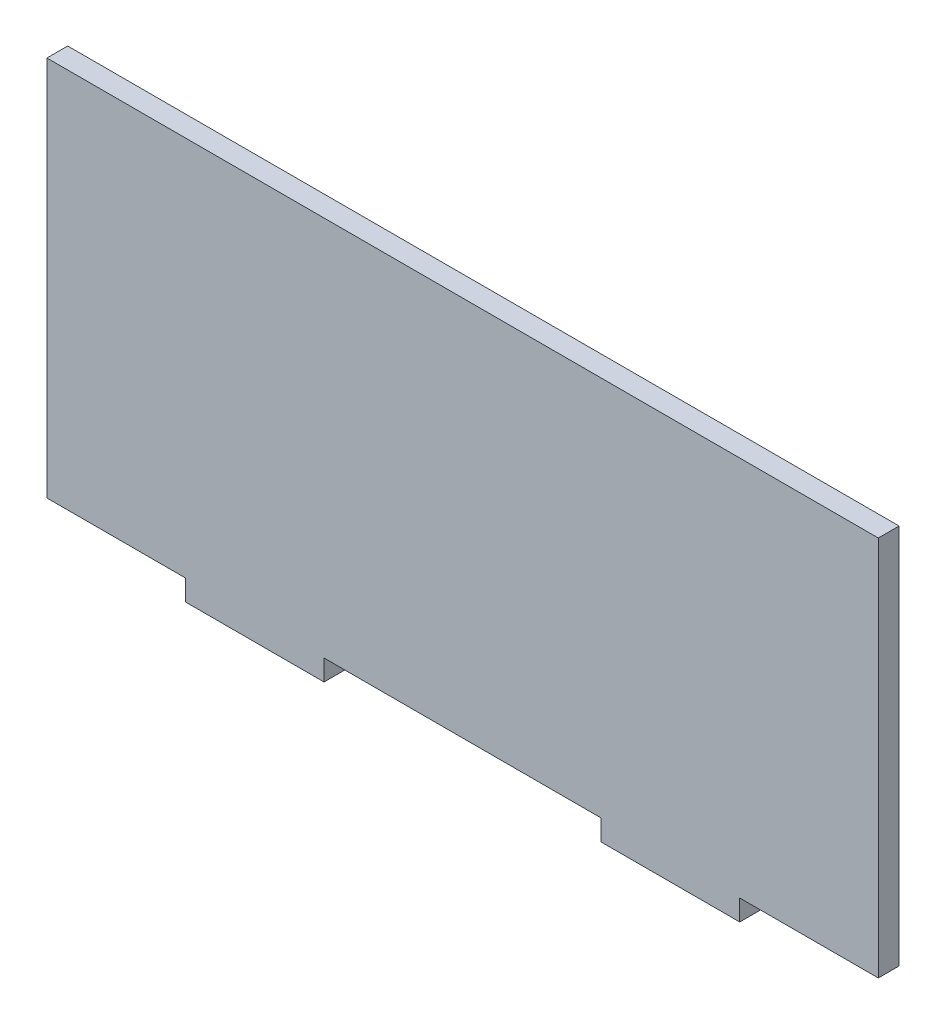
SolidWorks part; units mm, degrees
material "Acrylic (Medium-high impact)"
ref_plane "Front Plane" through (0, 0, 0) normal (0, 0, 1) x (1, 0, 0)
ref_plane "Top Plane" through (0, 0, 0) normal (0, 1, 0) x (1, 0, 0)
ref_plane "Right Plane" through (0, 0, 0) normal (1, 0, 0) x (0, 0, -1)
sketch "Sketch1" plane through (0, 0, 0) normal (0, 0, 1) x (1, 0, 0)
  line L1 (0, 0) -> (120, 0)
  line L2 (0, 0) -> (0, 55)
  line L3 (0, 55) -> (120, 55)
  line L4 (120, 0) -> (120, 55)
  dimension "D1" = 120
  dimension "D2" = 55
extrude "Boss-Extrude1" add sketch "Sketch1" against normal blind 3
sketch "Sketch2" plane through (0, 0, 0) normal (0, 0, 1) x (1, 0, 0)
  line L0 (0, 0) -> (120, 0) construction
  line L1 (20, 0) -> (40, 0)
  line L2 (20, 0) -> (20, -3)
  line L3 (20, -3) -> (40, -3)
  line L4 (40, 0) -> (40, -3)
  line L6 (80, 0) -> (100, 0)
  line L7 (80, 0) -> (80, -3)
  line L8 (80, -3) -> (100, -3)
  line L9 (100, 0) -> (100, -3)
  dimension "D1" = 3
  dimension "D2" = 3
  dimension "D3" = 20
  dimension "D4" = 20
  dimension "D5" = 20
  dimension "D6" = 20
extrude "Boss-Extrude2" add sketch "Sketch2" against normal blind 3
